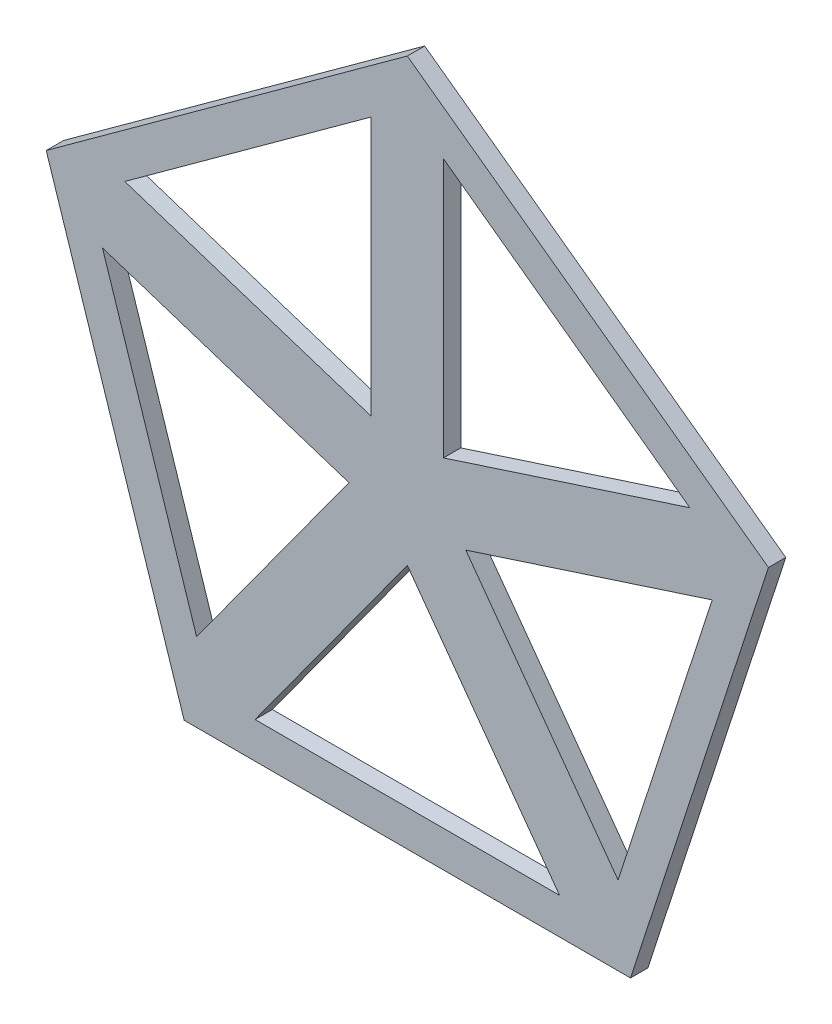
SolidWorks part; units mm, degrees
ref_plane "Front Plane" through (0, 0, 0) normal (0, 0, 1) x (1, 0, 0)
ref_plane "Top Plane" through (0, 0, 0) normal (0, 1, 0) x (1, 0, 0)
ref_plane "Right Plane" through (0, 0, 0) normal (1, 0, 0) x (0, 0, -1)
sketch "Sketch1" plane through (0, 0, 0) normal (0, 0, 1) x (1, 0, 0)
  line L0 (0, 26.2866) -> (0, 0) construction
  line L1 (0, 26.2866) -> (-25, 8.123)
  line L2 (-25, 8.123) -> (-15.4508, -21.2663)
  line L3 (-15.4508, -21.2663) -> (15.4508, -21.2663)
  line L4 (15.4508, -21.2663) -> (25, 8.123)
  line L5 (25, 8.123) -> (0, 26.2866)
  line L12 (-25, 8.123) -> (0, 0) construction
  line L13 (-15.4508, -21.2663) -> (0, 0) construction
  line L14 (15.4508, -21.2663) -> (0, 0) construction
  line L15 (25, 8.123) -> (0, 0) construction
  line L16 (-24.2275, 10.5006) -> (0.7725, 2.3776) construction
  line L17 (-21.1062, 4.2292) -> (-4.0451, -1.3143)
  line L19 (14.5894, -15.8273) -> (21.1062, 4.2292)
  line L20 (-19.5611, 8.9844) -> (-2.5, 3.441)
  line L21 (2.5, 21.38) -> (2.5, 3.441)
  line L22 (-2.5, 21.38) -> (-19.5611, 8.9844)
  line L23 (-25.7725, 5.7454) -> (-0.7725, -2.3776) construction
  line L25 (2.5, 26.2866) -> (2.5, 0) construction
  line L26 (19.5611, 8.9844) -> (2.5, 3.441)
  line L27 (23.5305, 6.1004) -> (-1.4695, 24.264) construction
  line L28 (-10.5443, -18.7663) -> (0, -4.2533)
  line L29 (14.5894, -15.8273) -> (4.0451, -1.3143)
  line L30 (-2.5, 21.38) -> (-2.5, 3.441)
  line L31 (-21.1062, 4.2292) -> (-14.5894, -15.8273)
  line L32 (21.1062, 4.2292) -> (4.0451, -1.3143)
  line L34 (19.5611, 8.9844) -> (2.5, 21.38)
  line L35 (-22.6224, 8.8955) -> (-13.0732, -20.4937) construction
  line L36 (-14.5894, -15.8273) -> (-4.0451, -1.3143)
  line L37 (10.5443, -18.7663) -> (0, -4.2533)
  line L39 (-10.5443, -18.7663) -> (10.5443, -18.7663)
  circle A0 centre (0, 0) radius 21.2663 construction
  dimension "D1" = 50
  dimension "D2" = 47.5528
  dimension "D3" = 29.3893
  dimension "D4" = 9.5492
  dimension "D5" = 25
  dimension "D6" = 40.4508
  dimension "D7" = 21.2663
  dimension "D10" = 54
extrude "Boss-Extrude1" add sketch "Sketch1" along normal blind 1.2
